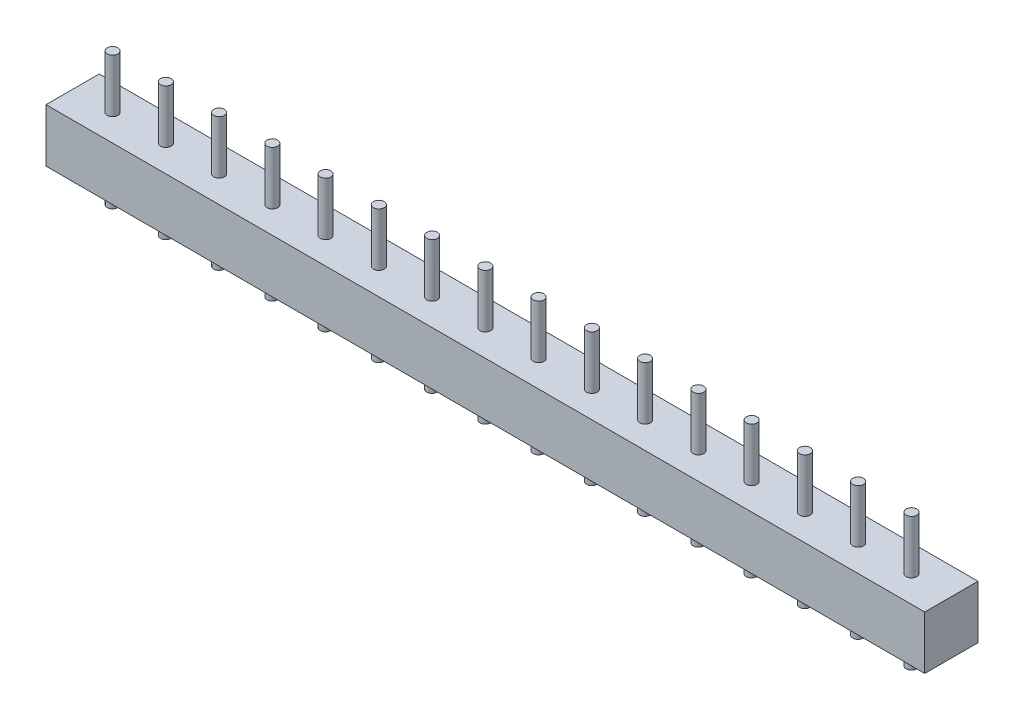
SolidWorks part; units mm, degrees
ref_plane "Front Plane" through (0, 0, 0) normal (0, 0, 1) x (1, 0, 0)
ref_plane "Top Plane" through (0, 0, 0) normal (0, 1, 0) x (1, 0, 0)
ref_plane "Right Plane" through (0, 0, 0) normal (1, 0, 0) x (0, 0, -1)
sketch "Sketch1" plane through (0, 0, 0) normal (0, 1, 0) x (1, 0, 0)
  line L7 (-20.955, 1.27) -> (20.955, 1.27)
  line L8 (-20.955, 1.27) -> (-20.955, -1.27)
  line L9 (-20.955, -1.27) -> (20.955, -1.27)
  line L10 (20.955, 1.27) -> (20.955, -1.27)
  line L11 (-20.955, 1.27) -> (20.955, -1.27) construction
  line L12 (-20.955, -1.27) -> (20.955, 1.27) construction
  dimension "D1" = 2.54
  dimension "D2" = 41.91
extrude "Extrude1" add sketch "Sketch1" along normal blind 2.54
sketch "Sketch2" plane through (0, 0, 0) normal (0, 1, 0) x (1, 0, 0)
  line L0 (20.955, -1.27) -> (20.955, 1.27) construction
  circle A0 centre (19.05, 0) radius 0.254
  circle A1 centre (16.51, 0) radius 0.254
  circle A2 centre (13.97, 0) radius 0.254
  circle A3 centre (11.43, 0) radius 0.254
  circle A4 centre (8.89, 0) radius 0.254
  circle A5 centre (6.35, 0) radius 0.254
  circle A6 centre (3.81, 0) radius 0.254
  circle A7 centre (1.27, 0) radius 0.254
  circle A8 centre (-1.27, 0) radius 0.254
  circle A9 centre (-3.81, 0) radius 0.254
  circle A10 centre (-6.35, 0) radius 0.254
  circle A11 centre (-8.89, 0) radius 0.254
  circle A12 centre (-11.43, 0) radius 0.254
  circle A13 centre (-13.97, 0) radius 0.254
  circle A14 centre (-16.51, 0) radius 0.254
  circle A15 centre (-19.05, 0) radius 0.254
  dimension "D1" = 0.508
  dimension "D2" = 1.905
extrude "Extrude2" add sketch "Sketch2" against normal blind 1.27
sketch "Sketch3" plane through (0, 2.54, 0) normal (0, 1, 0) x (1, 0, 0)
  circle A1 centre (6.35, 0) radius 0.254
  circle A2 centre (6.35, 0) radius 0.254
  circle A3 centre (8.89, 0) radius 0.254
  circle A4 centre (8.89, 0) radius 0.254
  circle A5 centre (11.43, 0) radius 0.254
  circle A6 centre (11.43, 0) radius 0.254
  circle A7 centre (13.97, 0) radius 0.254
  circle A8 centre (13.97, 0) radius 0.254
  circle A9 centre (16.51, 0) radius 0.254
  circle A10 centre (16.51, 0) radius 0.254
  circle A11 centre (19.05, 0) radius 0.254
  circle A12 centre (19.05, 0) radius 0.254
  circle A13 centre (-13.97, 0) radius 0.254
  circle A14 centre (-13.97, 0) radius 0.254
  circle A15 centre (-11.43, 0) radius 0.254
  circle A16 centre (-11.43, 0) radius 0.254
  circle A17 centre (-8.89, 0) radius 0.254
  circle A18 centre (-8.89, 0) radius 0.254
  circle A19 centre (-6.35, 0) radius 0.254
  circle A20 centre (-6.35, 0) radius 0.254
  circle A21 centre (-3.81, 0) radius 0.254
  circle A22 centre (-3.81, 0) radius 0.254
  circle A23 centre (-1.27, 0) radius 0.254
  circle A24 centre (-1.27, 0) radius 0.254
  circle A25 centre (1.27, 0) radius 0.254
  circle A26 centre (1.27, 0) radius 0.254
  circle A27 centre (3.81, 0) radius 0.254
  circle A28 centre (3.81, 0) radius 0.254
  circle A29 centre (-19.05, 0) radius 0.254
  circle A30 centre (-19.05, 0) radius 0.254
  circle A31 centre (-16.51, 0) radius 0.254
  circle A32 centre (-16.51, 0) radius 0.254
  dimension "D1" = 0
  dimension "D2" = 0
  dimension "D3" = 0
  dimension "D4" = 0
  dimension "D5" = 0
  dimension "D6" = 0
  dimension "D7" = 0
  dimension "D8" = 0
  dimension "D9" = 0
  dimension "D10" = 0
  dimension "D11" = 0
  dimension "D12" = 0
  dimension "D13" = 0
  dimension "D14" = 0
  dimension "D15" = 0
  dimension "D16" = 0
extrude "Extrude4" add sketch "Sketch3" along normal blind 2.54
